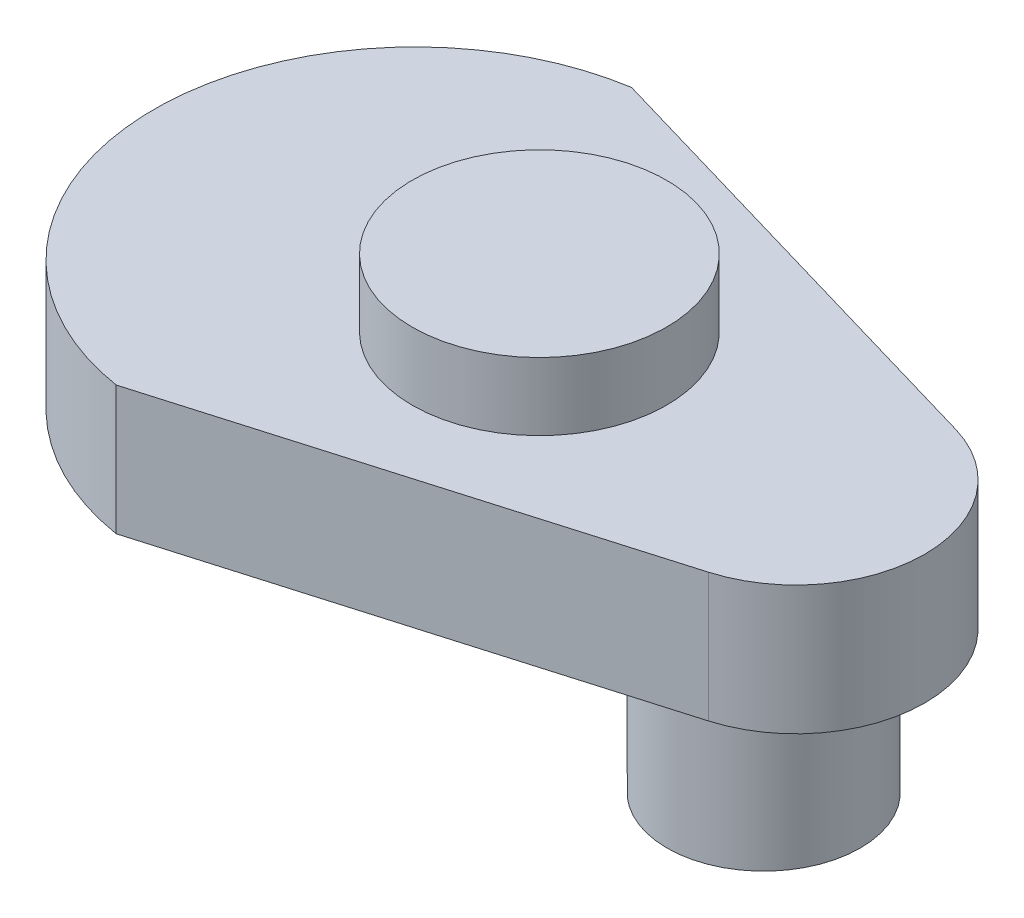
SolidWorks part; units mm, degrees
material "AISI 1045 Steel, cold drawn"
ref_plane "Front Plane" through (0, 0, 0) normal (0, 0, 1) x (1, 0, 0)
ref_plane "Top Plane" through (0, 0, 0) normal (0, 1, 0) x (1, 0, 0)
ref_plane "Right Plane" through (0, 0, 0) normal (1, 0, 0) x (0, 0, -1)
sketch "Sketch8" plane through (0, 0, 0) normal (0, 1, 0) x (1, 0, 0)
  line L0 (0, 0) -> (85.43, 0)
  line L1 (85.43, 0) -> (17.0633, 0)
  line L2 (17.0633, 0) -> (17.0633, 20)
  line L3 (17.0633, 0) -> (17.0633, -20)
  line L4 (17.0633, 20) -> (85.43, 0)
  line L5 (85.43, 0) -> (17.0633, -20)
  arc A0 (17.0633, 20) -> (17.0633, -20) centre (20.2527, 0) ccw
extrude "Boss-Extrude9" add sketch "Sketch8" along normal blind 10 contours L4 L2 L0 | L2 A0 L0 | L0 A0 L3 | L5 L0 L3
fillet "Fillet8" radius 10 1 edges at (85.43, 5, 0)
sketch "Sketch11" plane through (0, 10, 0) normal (0, 1, 0) x (1, 0, 0)
  line L0 (0, 0) -> (59.814, 0)
  line L1 (59.814, 0) -> (29.907, 0)
  arc A0 (17.0633, 20) -> (17.0633, -20) centre (20.2527, 0) ccw construction
  arc A1 (52.6217, -9.5977) -> (52.6217, 9.5977) centre (49.814, 0) ccw construction
  circle A2 centre (29.907, 0) radius 9.875
extrude "Boss-Extrude10" add sketch "Sketch11" along normal blind 5 contours L0 A2 | L0 A2
sketch "Sketch12" plane through (0, 0, 0) normal (0, -1, 0) x (1, 0, 0)
  line L0 (59.814, 0) -> (47.314, 0)
  arc A0 (52.6217, -9.5977) -> (52.6217, 9.5977) centre (49.814, 0) ccw construction
  circle A1 centre (47.314, 0) radius 7.5
extrude "Boss-Extrude11" add sketch "Sketch12" along normal blind 12.5
sketch "Sketch14" plane through (0, 15, 0) normal (0, 1, 0) x (1, 0, 0)
  circle A0 centre (29.907, 0) radius 9.875
extrude "Boss-Extrude12" add sketch "Sketch14" along normal blind 0.25
sketch "Sketch15" plane through (0, -12.5, 0) normal (0, -1, 0) x (1, 0, 0)
  circle A0 centre (47.314, 0) radius 7.5
extrude "Cut-Extrude1" cut sketch "Sketch15" against normal blind 0.25
sketch "Sketch18" plane through (0, -12.25, 0) normal (0, -1, 0) x (1, 0, 0)
  circle A0 centre (47.314, 0) radius 7.5
extrude "Cut-Extrude2" cut sketch "Sketch18" against normal blind 12
sketch "Sketch19" plane through (0, -0.25, 0) normal (0, -1, 0) x (1, 0, 0)
  circle A0 centre (47.314, 0) radius 7.5
extrude "Boss-Extrude13" add sketch "Sketch19" along normal blind 12
